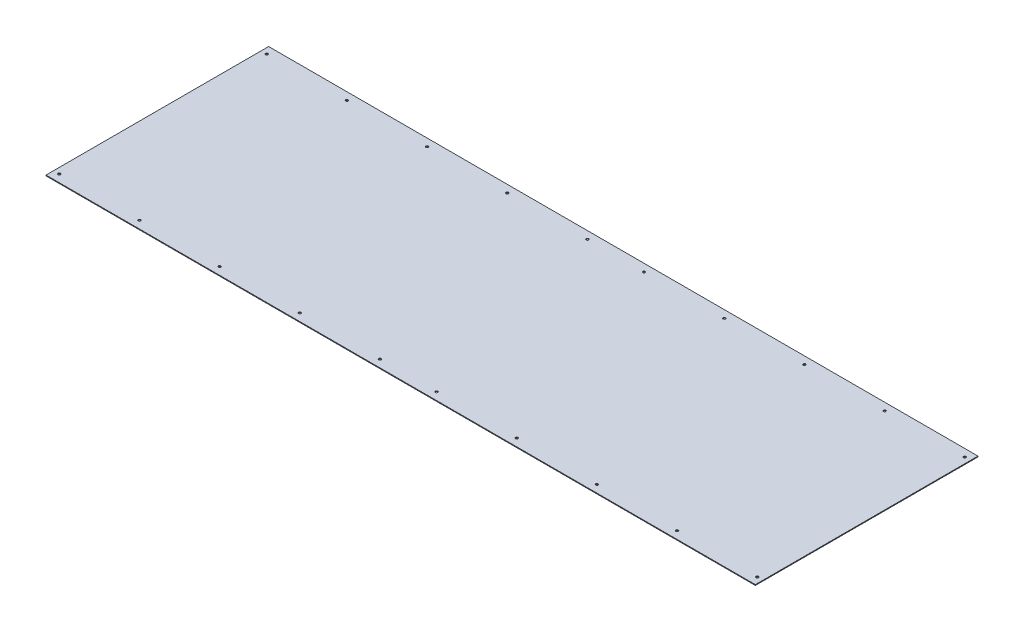
SolidWorks part; units mm, degrees
material "5052-H32"
ref_plane "Front Plane" through (0, 0, 0) normal (0, 0, 1) x (1, 0, 0)
ref_plane "Top Plane" through (0, 0, 0) normal (0, 1, 0) x (1, 0, 0)
ref_plane "Right Plane" through (0, 0, 0) normal (1, 0, 0) x (0, 0, -1)
sketch "Sketch1" plane through (0, 0, 0) normal (0, 1, 0) x (1, 0, 0)
  line L1 (940, -295) -> (-940, -295)
  line L2 (940, -295) -> (940, 295)
  line L3 (940, 295) -> (-940, 295)
  line L4 (-940, -295) -> (-940, 295)
  line L5 (940, -295) -> (-940, 295) construction
  line L6 (940, 295) -> (-940, -295) construction
  point P0 (0, 0)
  dimension "D1" = 590
  dimension "D2" = 1880
extrude "Boss-Extrude1" add sketch "Sketch1" along normal blind 2
sketch "Sketch3" plane through (0, 2, 0) normal (0, 1, 0) x (1, 0, 0)
  line L0 (-940, 295) -> (-940, -295) construction
  line L1 (940, 295) -> (-940, 295) construction
  line L2 (-940, -295) -> (940, -295) construction
  line L3 (940, -295) -> (940, 295) construction
  circle A0 centre (-925, 275) radius 3.25
  circle A1 centre (-925, -275) radius 3.25
  circle A2 centre (-712.5, 275) radius 3.25
  circle A3 centre (-712.5, -275) radius 3.25
  circle A4 centre (-500, 275) radius 3.25
  circle A5 centre (-500, -275) radius 3.25
  circle A6 centre (-287.5, 275) radius 3.25
  circle A7 centre (-287.5, -275) radius 3.25
  circle A8 centre (-75, 275) radius 3.25
  circle A9 centre (-75, -275) radius 3.25
  circle A10 centre (925, 275) radius 3.25
  circle A11 centre (925, -275) radius 3.25
  circle A12 centre (712.5, 275) radius 3.25
  circle A13 centre (712.5, -275) radius 3.25
  circle A14 centre (500, 275) radius 3.25
  circle A15 centre (500, -275) radius 3.25
  circle A16 centre (287.5, 275) radius 3.25
  circle A17 centre (287.5, -275) radius 3.25
  circle A18 centre (75, 275) radius 3.25
  circle A19 centre (75, -275) radius 3.25
  dimension "D2" = 6.5
  dimension "D9" = 6.5
  dimension "D1" = 15
  dimension "D3" = 20
  dimension "D4" = 20
  dimension "D6" = 20
  dimension "D7" = 20
  dimension "D8" = 15
  dimension "D11" = 212.5
  dimension "D12" = 212.5
  dimension "D5" = 5
  dimension "D10" = 5
extrude "Cut-Extrude1" cut sketch "Sketch3" against normal blind 10
